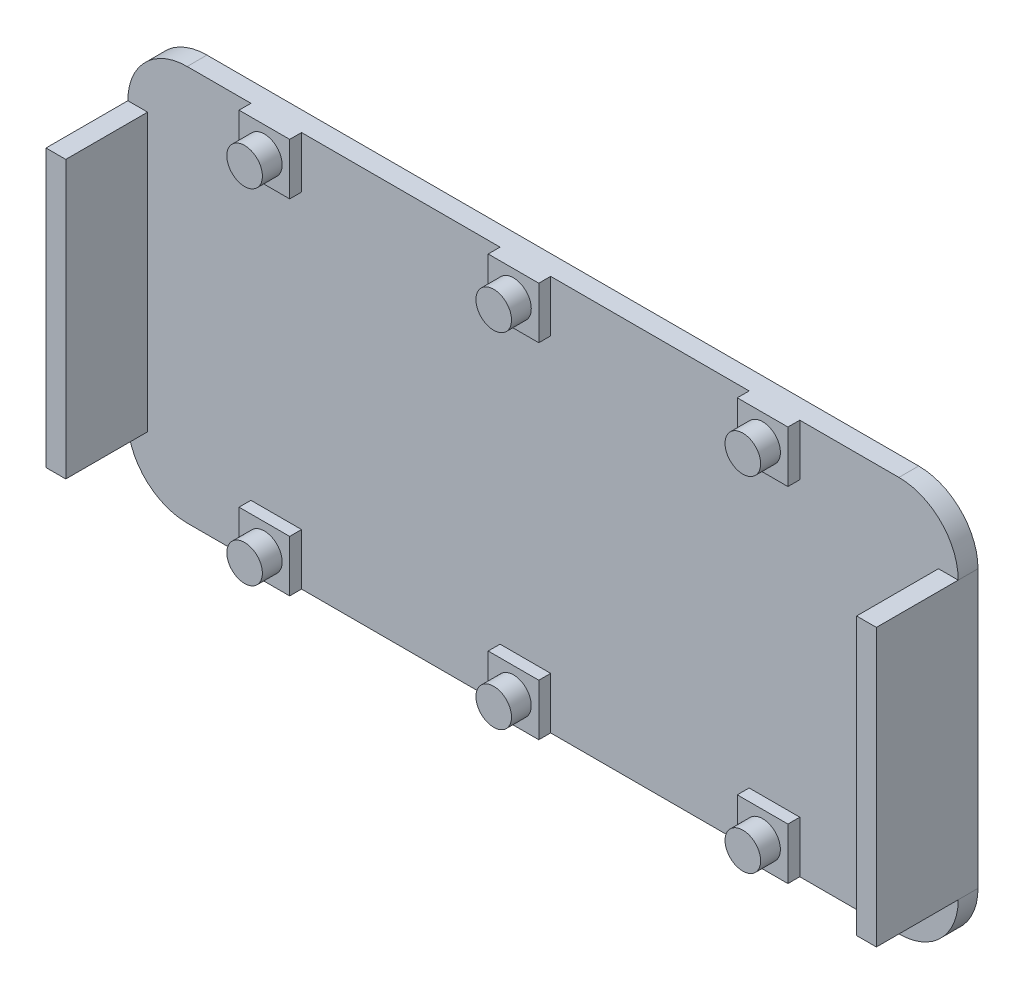
SolidWorks part; units mm, degrees
ref_plane "Front Plane" through (0, 0, 0) normal (0, 0, 1) x (1, 0, 0)
ref_plane "Top Plane" through (0, 0, 0) normal (0, 1, 0) x (1, 0, 0)
ref_plane "Right Plane" through (0, 0, 0) normal (1, 0, 0) x (0, 0, -1)
sketch "Sketch1" plane through (0, 0, 0) normal (0, 0, 1) x (1, 0, 0)
  line L1 (-90, -50) -> (90, -50)
  line L2 (-105, -35) -> (-105, 35)
  line L3 (-90, 50) -> (90, 50)
  line L4 (105, -35) -> (105, 35)
  line L5 (-105, -50) -> (105, 50) construction
  line L6 (-105, 50) -> (105, -50) construction
  arc A0 (-105, -35) -> (-90, -50) centre (-90, -35) ccw
  arc A1 (90, -50) -> (105, -35) centre (90, -35) ccw
  arc A2 (105, 35) -> (90, 50) centre (90, 35) ccw
  arc A3 (-90, 50) -> (-105, 35) centre (-90, 35) ccw
  point P0 (0, 0)
  dimension "D3" = 15
  dimension "D1" = 210
  dimension "D2" = 100
extrude "Boss-Extrude1" add sketch "Sketch1" along normal blind 5
sketch "Sketch2" plane through (0, 0, 5) normal (0, 0, 1) x (1, 0, 0)
  line L0 (-105, 0) -> (105, 0) construction
  line L1 (-105, 35) -> (-105, -35) construction
  line L2 (105, -35) -> (105, 35) construction
  line L3 (90, 50) -> (-90, 50) construction
  line L4 (-73.8737, -0.1228) -> (-73.8737, 43.4772) construction
  line L5 (-73.8737, 36.9543) -> (-61.0737, 36.9543)
  line L6 (-73.8737, 43.4772) -> (-67.4737, 43.4772) construction
  line L7 (-73.8737, 36.9543) -> (-73.8737, 50)
  line L8 (-73.8737, 50) -> (-61.0737, 50)
  line L9 (-61.0737, 36.9543) -> (-61.0737, 50)
  line L10 (-73.8737, 36.9543) -> (-61.0737, 50) construction
  line L11 (-73.8737, 50) -> (-61.0737, 36.9543) construction
  line L12 (-10.8737, 36.9543) -> (-10.8737, 50)
  line L13 (-10.8737, 36.9543) -> (1.9263, 36.9543)
  line L14 (1.9263, 36.9543) -> (1.9263, 50)
  line L15 (-10.8737, 50) -> (1.9263, 50)
  line L16 (52.1263, 36.9543) -> (52.1263, 50)
  line L17 (52.1263, 36.9543) -> (64.9263, 36.9543)
  line L18 (64.9263, 36.9543) -> (64.9263, 50)
  line L19 (52.1263, 50) -> (64.9263, 50)
  line L20 (-73.8737, -50) -> (-61.0737, -50)
  line L21 (-61.0737, -36.9543) -> (-61.0737, -50)
  line L22 (-73.8737, -36.9543) -> (-61.0737, -36.9543)
  line L23 (-73.8737, -36.9543) -> (-73.8737, -50)
  line L24 (-10.8737, -36.9543) -> (1.9263, -36.9543)
  line L25 (1.9263, -36.9543) -> (1.9263, -50)
  line L26 (-10.8737, -50) -> (1.9263, -50)
  line L27 (-10.8737, -36.9543) -> (-10.8737, -50)
  line L28 (52.1263, -36.9543) -> (64.9263, -36.9543)
  line L29 (64.9263, -36.9543) -> (64.9263, -50)
  line L30 (52.1263, -50) -> (64.9263, -50)
  line L31 (52.1263, -36.9543) -> (52.1263, -50)
  dimension "D3" = 12.8
  dimension "D1" = 43.6
  dimension "D2" = 6.4
  dimension "D4" = 3
sketch "Sketch3" plane through (0, 0, 5) normal (0, 0, 1) x (1, 0, 0)
  line L0 (-105, 0) -> (-102.5, 0) construction
  line L1 (-105, 35) -> (-105, -35) construction
  line L2 (0, 50) -> (0, -50) construction
  line L3 (90, 50) -> (-90, 50) construction
  line L4 (-90, -50) -> (90, -50) construction
  line L5 (100, 35) -> (105, 35)
  line L6 (-100, -35) -> (-105, -35)
  line L7 (-100, -35) -> (-100, 35)
  line L8 (-100, 35) -> (-105, 35)
  line L9 (-105, -35) -> (-105, 35)
  line L10 (-100, -35) -> (-105, 35) construction
  line L11 (-100, 35) -> (-105, -35) construction
  line L12 (105, -35) -> (105, 35)
  line L13 (100, -35) -> (105, -35)
  line L14 (100, -35) -> (100, 35)
  line L15 (100, 35) -> (105, -35) construction
  line L16 (100, -35) -> (105, 35) construction
  point P20 (102.5, 0)
  dimension "D1" = 2.5
extrude "Boss-Extrude3" add sketch "Sketch3" along normal blind 20.7
extrude "Boss-Extrude4" add sketch "Sketch2" along normal blind 3
sketch "Sketch4" plane through (0, 0, 8) normal (0, 0, 1) x (1, 0, 0)
  line L0 (-67.4737, 50) -> (-67.4737, 36.9543) construction
  line L1 (-61.0737, 50) -> (-73.8737, 50) construction
  line L2 (-73.8737, 36.9543) -> (-61.0737, 36.9543) construction
  line L3 (-100.1246, 0) -> (98.9272, 0) construction
  circle A0 centre (-67.4737, 43.4772) radius 4.5
  circle A1 centre (-4.4737, 43.4772) radius 4.5
  circle A2 centre (58.5263, 43.4772) radius 4.5
  circle A3 centre (58.5263, -43.4772) radius 4.5
  circle A4 centre (-4.4737, -43.4772) radius 4.5
  circle A5 centre (-67.4737, -43.4772) radius 4.5
  dimension "D1" = 3
extrude "Boss-Extrude5" add sketch "Sketch4" along normal blind 5
sketch "Sketch5" plane through (0, 0, 5) normal (0, 0, 1) x (1, 0, 0)
  line L0 (27.0263, 50) -> (27.0263, -50) construction
  line L1 (52.1263, 50) -> (1.9263, 50) construction
  line L2 (1.9263, -50) -> (52.1263, -50) construction
  line L3 (1.9263, 50) -> (1.9263, 36.9543) construction
  line L4 (1.9263, -36.9543) -> (1.9263, -50) construction
  line L5 (-10.8737, 50) -> (-10.8737, 36.9543) construction
  line L6 (-10.8737, 50) -> (-10.8737, 36.9543) construction
  line L7 (-10.8737, 50) -> (-61.0737, 50) construction
